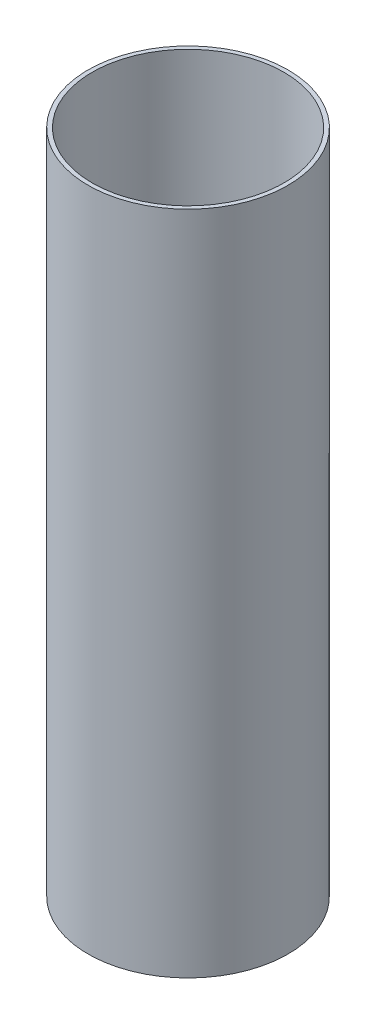
SolidWorks part; units mm, degrees
material "Hexcel AS4C (3000 Filaments)"
ref_plane "Front Plane" through (0, 0, 0) normal (0, 0, 1) x (1, 0, 0)
ref_plane "Top Plane" through (0, 0, 0) normal (0, 1, 0) x (1, 0, 0)
ref_plane "Right Plane" through (0, 0, 0) normal (1, 0, 0) x (0, 0, -1)
sketch "Sketch2" plane through (0, 0, 0) normal (0, 0, 1) x (1, 0, 0)
  line L0 (0, 0) -> (0, 51.225) construction
  line L1 (26.9875, -29.8416) -> (28.1305, -29.8416)
  line L2 (26.9875, -29.8416) -> (26.9875, -217.1666)
  line L3 (26.9875, -217.1666) -> (28.1305, -217.1666)
  line L4 (28.1305, -29.8416) -> (28.1305, -217.1666)
revolve "Revolve1" add sketch "Sketch2" angle 360 about L0
